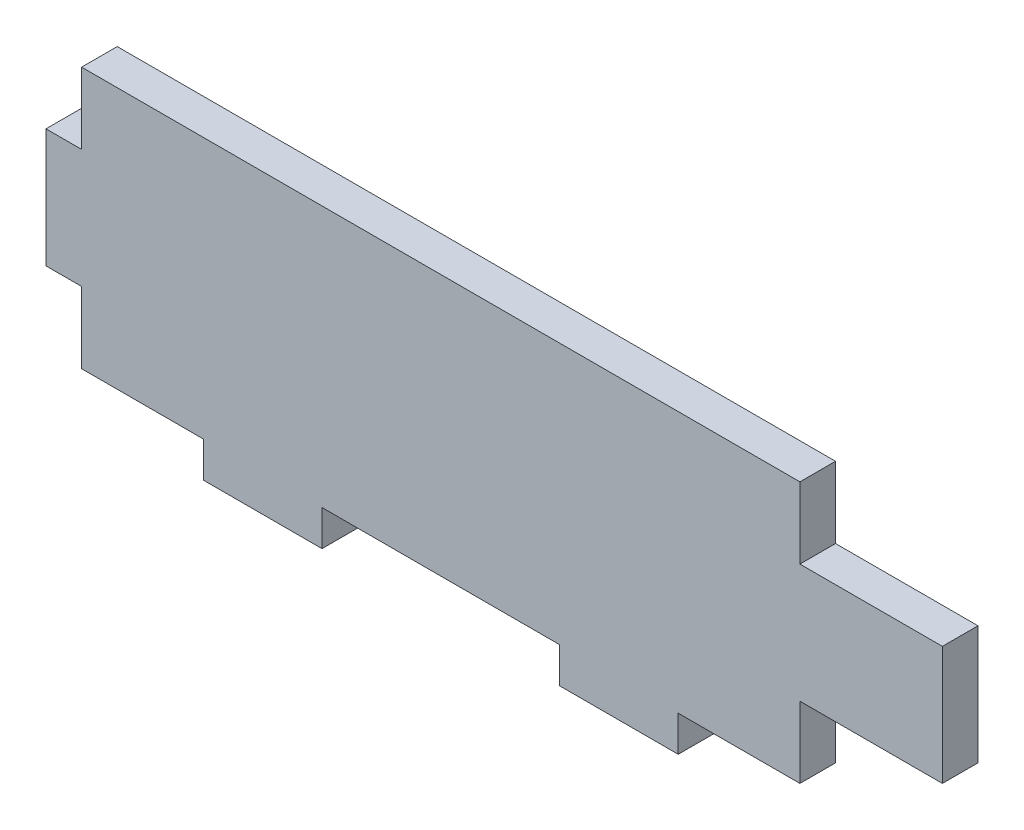
SolidWorks part; units mm, degrees
material "ABS PC"
ref_plane "Front Plane" through (0, 0, 0) normal (0, 0, 1) x (1, 0, 0)
ref_plane "Top Plane" through (0, 0, 0) normal (0, 1, 0) x (1, 0, 0)
ref_plane "Right Plane" through (0, 0, 0) normal (1, 0, 0) x (0, 0, -1)
sketch "Sketch1" plane through (0, 0, 0) normal (0, 0, 1) x (1, 0, 0)
  line L0 (-30.25, 11) -> (30.25, 11)
  line L1 (30.25, 11) -> (30.25, 5)
  line L2 (30.25, 5) -> (45.25, 5)
  line L3 (45.25, 5) -> (45.25, -5)
  line L4 (45.25, -5) -> (30.25, -5)
  line L5 (30.25, -5) -> (30.25, -11)
  line L6 (30.25, -11) -> (20, -11)
  line L7 (20, -11) -> (20, -14)
  line L8 (20, -14) -> (10, -14)
  line L9 (10, -14) -> (10, -11)
  line L10 (10, -11) -> (-10, -11)
  line L11 (-10, -11) -> (-10, -14)
  line L12 (-10, -14) -> (-20, -14)
  line L13 (-20, -14) -> (-20, -11)
  line L14 (-20, -11) -> (-30.25, -11)
  line L15 (-30.25, -11) -> (-30.25, -5)
  line L16 (-30.25, -5) -> (-33.25, -5)
  line L17 (-33.25, -5) -> (-33.25, 5)
  line L18 (-33.25, 5) -> (-30.25, 5)
  line L19 (-30.25, 5) -> (-30.25, 11)
  line L20 (0, 11) -> (0, 0) construction
  line L21 (0, 0) -> (0, -11) construction
  line L27 (-32.25, 5) -> (-32.25, -5) construction
  line L28 (37.75, 5) -> (37.75, -5) construction
  dimension "D1" = 3
  dimension "D2" = 22
  dimension "D3" = 10
  dimension "D4" = 10
  dimension "D5" = 1
  dimension "D6" = 20
  dimension "D7" = 60.5
  dimension "D8" = 15
  dimension "D10" = 70
extrude "Boss-Extrude1" add sketch "Sketch1" along normal blind 3
ref_plane "Plane1" through (0, 0, 0) normal (-1, 0, 0) x (0, 0, 1)
sketch "Sketch2" plane through (0, 0, 3) normal (0, 0, 1) x (1, 0, 0)
  line L1 (45.25, 5) -> (42.25, 5)
  line L2 (45.25, 5) -> (45.25, -5)
  line L3 (45.25, -5) -> (42.25, -5)
  line L4 (42.25, 5) -> (42.25, -5)
  line L5 (30.25, -5) -> (45.25, -5) construction
  dimension "D1" = 3
extrude "Cut-Extrude1" cut sketch "Sketch2" against normal through all
